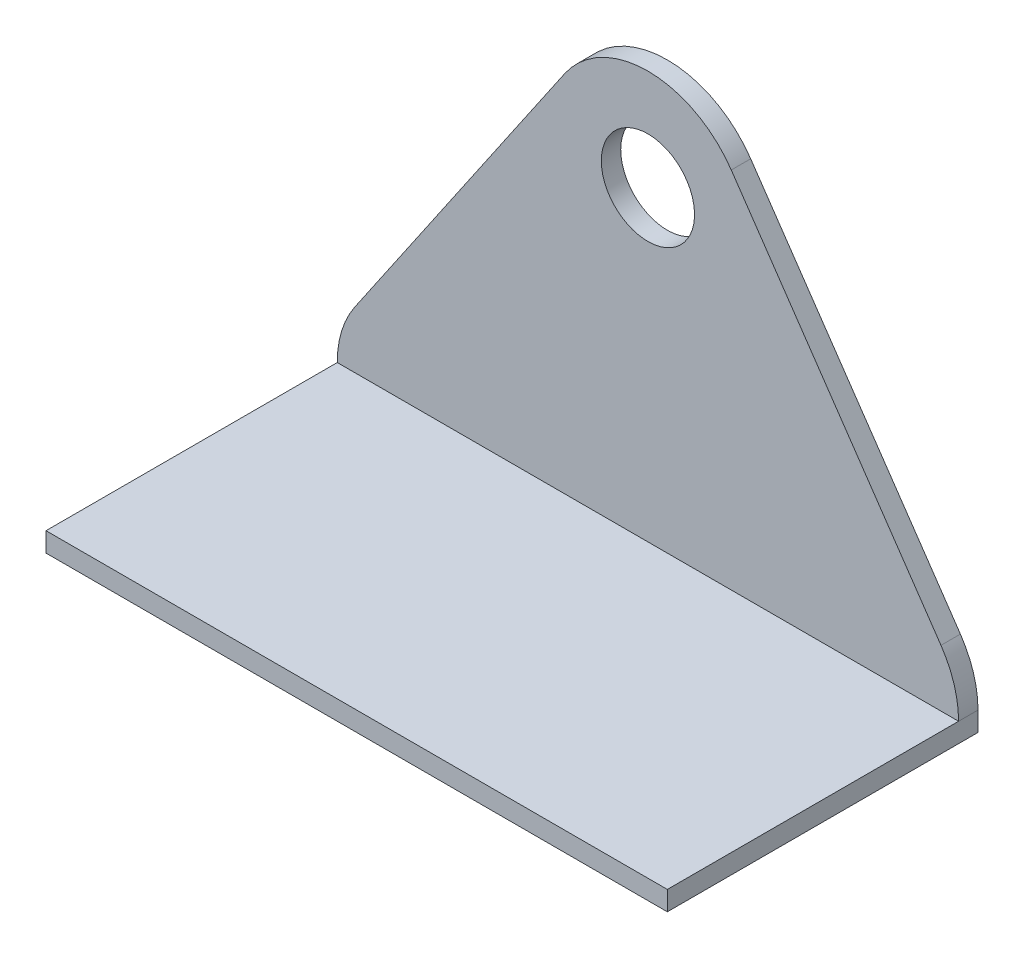
SolidWorks part; units mm, degrees
ref_plane "Front Plane" through (0, 0, 0) normal (0, 0, 1) x (1, 0, 0)
ref_plane "Top Plane" through (0, 0, 0) normal (0, 1, 0) x (1, 0, 0)
ref_plane "Right Plane" through (0, 0, 0) normal (1, 0, 0) x (0, 0, -1)
sketch "Sketch1" plane through (0, 0, 0) normal (0, 1, 0) x (1, 0, 0)
  line L1 (0, 0) -> (80, 0)
  line L2 (0, 0) -> (0, 40)
  line L3 (0, 40) -> (80, 40)
  line L4 (80, 0) -> (80, 40)
  dimension "D1" = 80
  dimension "D2" = 40
extrude "Boss-Extrude1" add sketch "Sketch1" along normal blind 2.5
sketch "Sketch3" plane through (0, 0, -40) normal (0, 0, -1) x (-1, 0, 0)
  line L0 (-80, 2.5) -> (-80, 0) construction
  line L1 (-40, 0) -> (-40, 55) construction
  line L2 (-80, 0) -> (0, 0) construction
  line L3 (-77.7323, 9.836) -> (-50.7323, 49.336)
  line L4 (-40, 55) -> (-21.4792, 55) construction
  line L5 (-2.2677, 9.836) -> (-29.2677, 49.336)
  line L6 (-80, 2.5) -> (0, 2.5)
  arc A0 (-80, 2.5) -> (-77.7323, 9.836) centre (-67, 2.5) cw
  arc A1 (-50.7323, 49.336) -> (-29.2677, 49.336) centre (-40, 42) cw
  arc A2 (0, 2.5) -> (-2.2677, 9.836) centre (-13, 2.5) ccw
  circle A3 centre (-40, 42) radius 6
  circle A5 centre (-40, 42) radius 6 construction
  line M3 (0, 2.5) -> (-80, 2.5)
  dimension "D1" = 13
  dimension "D2" = 55
extrude "Boss-Extrude2" add sketch "Sketch3" against normal blind 2.5 contours A2 L5 A1 L3 A0 A3 M3
